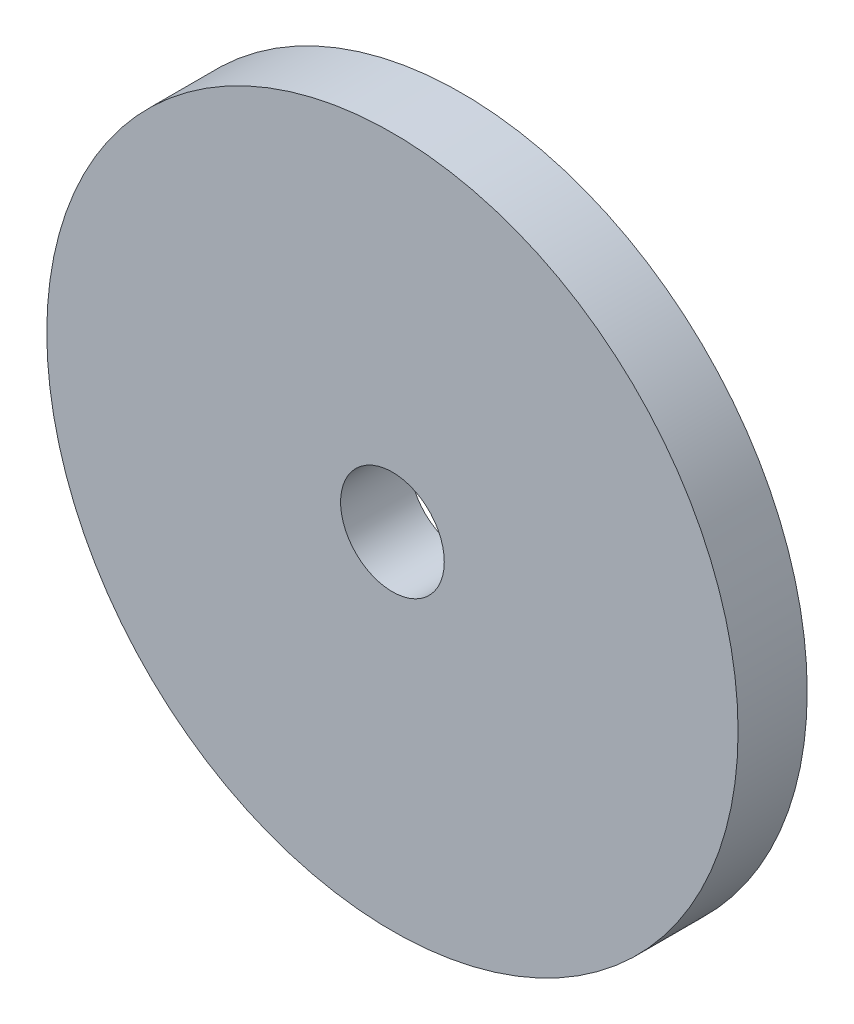
SolidWorks part; units mm, degrees
ref_plane "Piano frontale" through (0, 0, 0) normal (0, 0, 1) x (1, 0, 0)
ref_plane "Piano superiore" through (0, 0, 0) normal (0, 1, 0) x (1, 0, 0)
ref_plane "Piano destro" through (0, 0, 0) normal (1, 0, 0) x (0, 0, -1)
sketch "Sketch1" plane through (0, 0, 0) normal (0, 0, 1) x (1, 0, 0)
  circle A0 centre (0, 0) radius 10
  circle A1 centre (0, 0) radius 1.5
  dimension "D1" = 20
extrude "Boss-Extrude1" add sketch "Sketch1" along normal blind 2
